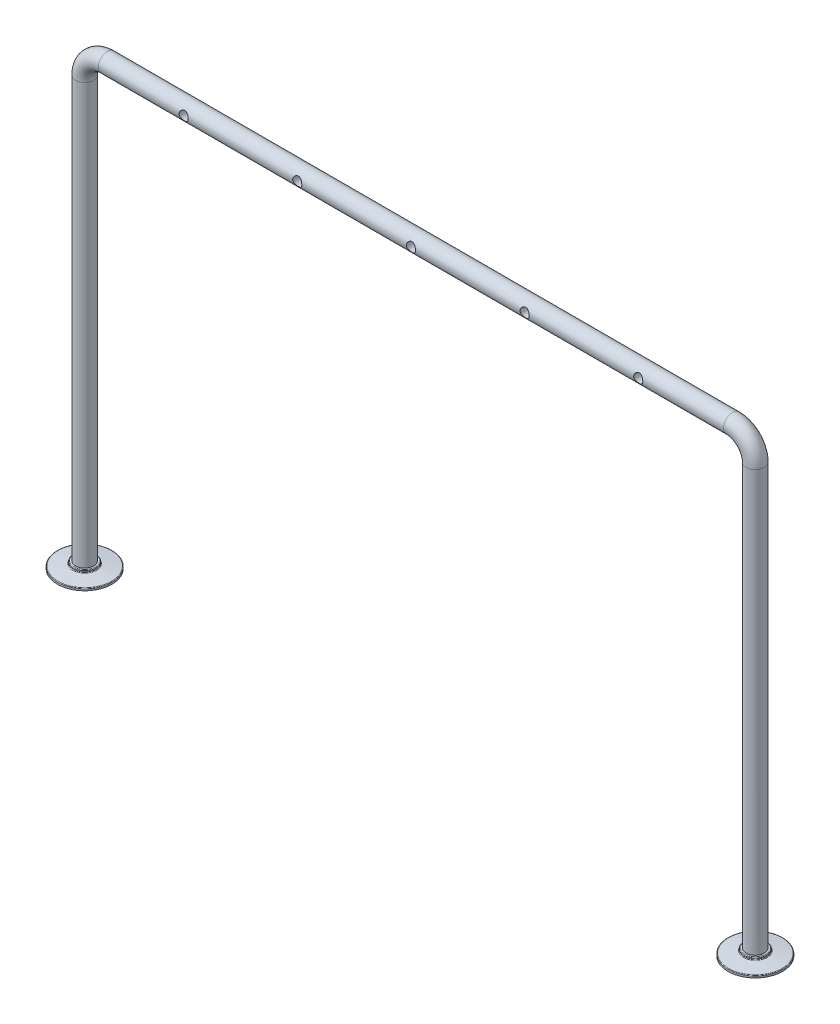
SolidWorks part; units mm, degrees
ref_plane "Front Plane" through (0, 0, 0) normal (0, 0, 1) x (1, 0, 0)
ref_plane "Top Plane" through (0, 0, 0) normal (0, 1, 0) x (1, 0, 0)
ref_plane "Right Plane" through (0, 0, 0) normal (1, 0, 0) x (0, 0, -1)
sketch "Sketch1" plane through (0, 0, 0) normal (0, 0, 1) x (1, 0, 0)
  line L0 (0, -1474.3902) -> (0, 2948.7805) construction
  line L1 (1475, 0) -> (1475, 1850)
  line L2 (1375, 1950) -> (-1375, 1950)
  line L3 (-1475, 1850) -> (-1475, 0)
  arc A0 (1475, 1850) -> (1375, 1950) centre (1375, 1850) ccw
  arc A1 (-1375, 1950) -> (-1475, 1850) centre (-1375, 1850) ccw
  point P9 (1475, 1950)
  point P12 (-1475, 1950)
  dimension "D3" = 100
  dimension "D1" = 1950
  dimension "D2" = 2950
sketch "Sketch2" plane through (0, 0, 0) normal (0, 1, 0) x (1, 0, 0)
  circle A1 centre (1475.076, 0) radius 40
  point P4 (0, 0)
  dimension "D2" = 80
sketch "Sketch3" plane through (0, 0, 0) normal (0, 1, 0) x (1, 0, 0)
  circle A0 centre (-1475, 0) radius 40
  dimension "D1" = 80
sweep "Sweep1" add profiles "Sketch3" path "Sketch1"
sketch "Sketch4" plane through (0, 0, 0) normal (0, 0, 1) x (1, 0, 0)
  line L0 (-1475, 0) -> (-1475, -67.2494) construction
  line L1 (-1515, 0) -> (-1435, 0) construction
  line L2 (-1475, 0) -> (-1475, -30)
  line L3 (-1475, -30) -> (-1595, -30)
  line L4 (-1595, -30) -> (-1595, -22.6019)
  line L5 (-1592.4243, -19.632) -> (-1527.5757, -10.368)
  line L6 (-1525, -7.3981) -> (-1525, -3)
  line L7 (-1522, 0) -> (-1475, 0)
  arc A0 (-1525, -3) -> (-1522, 0) centre (-1522, -3) cw
  arc A1 (-1527.5757, -10.368) -> (-1525, -7.3981) centre (-1528, -7.3981) ccw
  arc A2 (-1595, -22.6019) -> (-1592.4243, -19.632) centre (-1592, -22.6019) cw
  point P11 (-1525, 0)
  point P14 (-1525, -10)
  point P17 (-1595, -20)
  dimension "D6" = 3
  dimension "D1" = 30
  dimension "D2" = 50
  dimension "D3" = 120
  dimension "D4" = 10
  dimension "D5" = 10
revolve "Revolve1" add sketch "Sketch4" angle 360 about L0
mirror "Mirror1" about plane through (0, 0, 0) normal (1, 0, 0) of "Revolve1"
sketch "Sketch6" plane through (0, 0, 0) normal (0, 0, 1) x (1, 0, 0)
  line L0 (0, 0) -> (0, 1910) construction
  line L1 (-1375, 1910) -> (1375, 1910) construction
sketch "Sketch8" plane through (0, 0, 0) normal (0, 0, 1) x (1, 0, 0)
  line L0 (1375, 1950) -> (-1375, 1950) construction
  line L1 (0, -1474.3902) -> (0, 2948.7805) construction
  circle A0 centre (-1000, 1950) radius 20
  point P4 (0, 0)
  dimension "D1" = 40
  dimension "D2" = 1000
extrude "Cut-Extrude3" cut sketch "Sketch8" along normal blind 100
pattern_linear "LPattern1" count 5 spacing 500 along (1, 0, 0) of "Cut-Extrude3"
